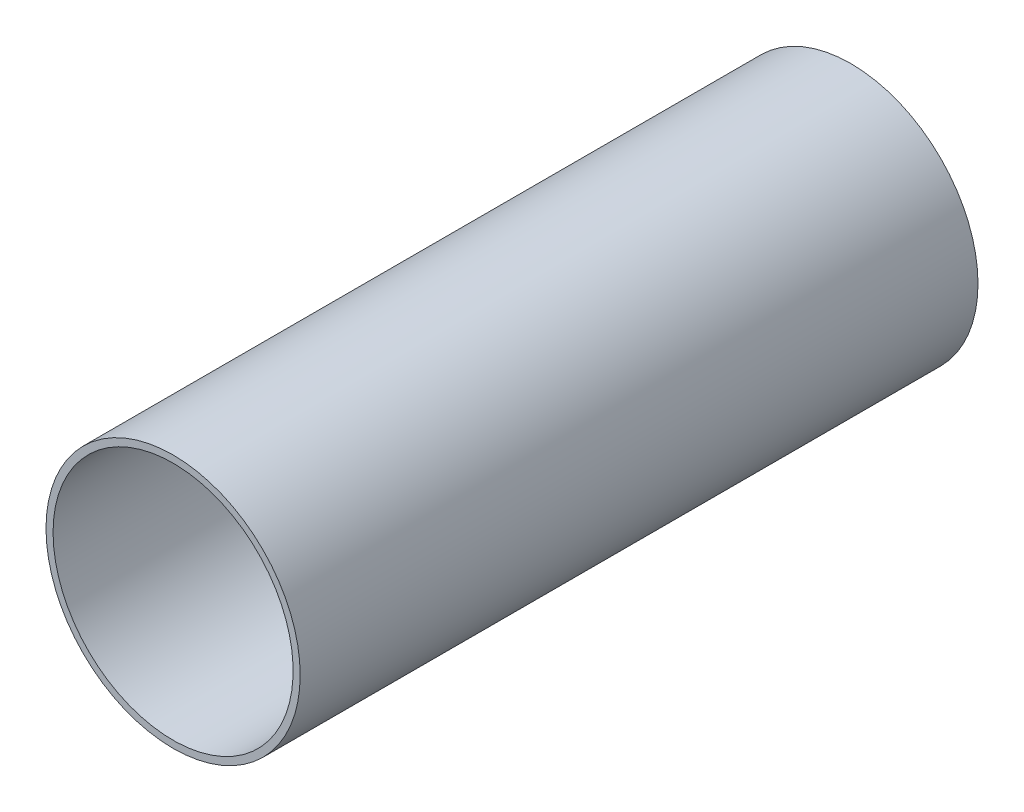
SolidWorks part; units mm, degrees
ref_plane "Front Plane" through (0, 0, 0) normal (0, 0, 1) x (1, 0, 0)
ref_plane "Top Plane" through (0, 0, 0) normal (0, 1, 0) x (1, 0, 0)
ref_plane "Right Plane" through (0, 0, 0) normal (1, 0, 0) x (0, 0, -1)
sketch "Sketch1" plane through (0, 0, 0) normal (0, 0, 1) x (1, 0, 0)
  circle A0 centre (0, 0) radius 53.975 construction
  circle A1 centre (0, 0) radius 57.15 construction
  point P4 (53.975, 0)
  point P5 (57.15, 0)
  dimension "ID" = 107.95
  dimension "OD" = 114.3
  dimension "Wall Thickness" = 3.175
sketch "Sketch2" plane through (0, 0, 0) normal (1, 0, 0) x (0, 0, -1)
  line L0 (-152.4, 0) -> (152.4, 0) construction
  line L1 (0, -57.15) -> (0, 57.15) construction
  line L2 (0, 57.15) -> (0, -57.15) construction
  point P0 (-23.8125, 0)
  point P4 (0, 0)
  point P8 (0, 0)
  point P13 (23.8125, 0)
  dimension "Length" = 304.8
  dimension "D1" = 128.5875
sketch "Sketch3" plane through (0, 0, 0) normal (0, 0, 1) x (1, 0, 0)
  circle A0 centre (0, 0) radius 53.975 construction
  circle A1 centre (0, 0) radius 57.15 construction
  circle A2 centre (0, 0) radius 53.975
  circle A3 centre (0, 0) radius 57.15
extrude "Boss-Extrude1" add sketch "Sketch3" along normal up to vertex (152.4 mm away) and the other way up to vertex (152.4 mm away) up to point (0, 0, 152.4) other way up to point (0, 0, -152.4)
equation "\"D1@Sketch2\"=\"OD@Sketch1\"*1.125"
